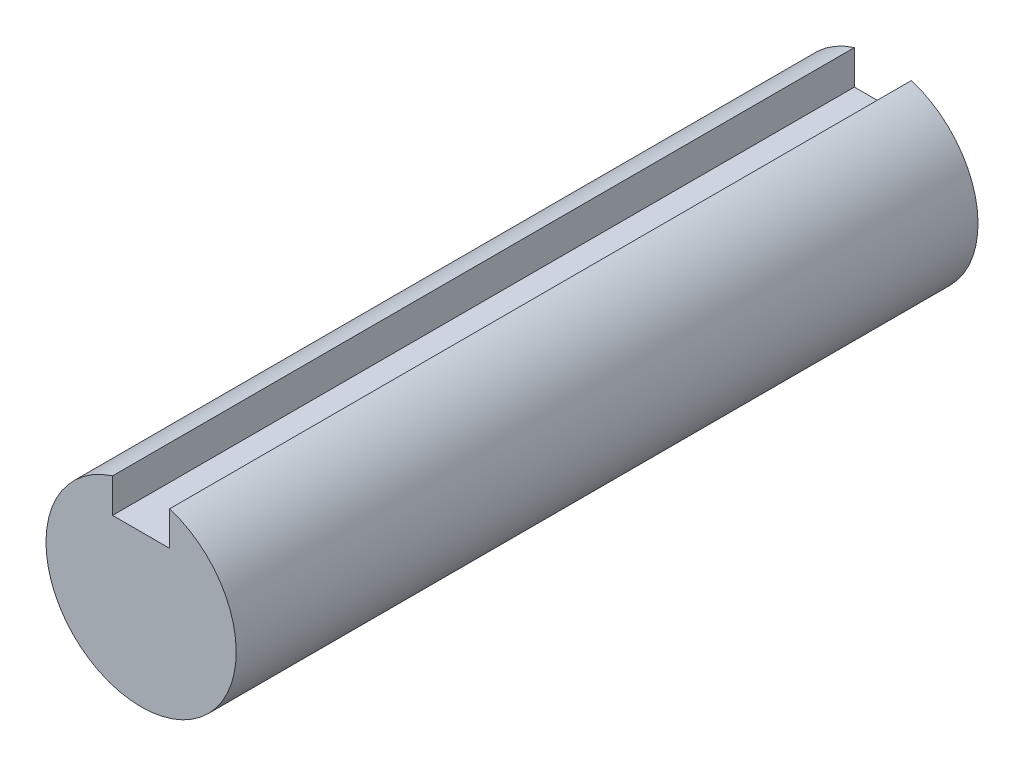
SolidWorks part; units mm, degrees
ref_plane "Piano frontale" through (0, 0, 0) normal (0, 0, 1) x (1, 0, 0)
ref_plane "Piano superiore" through (0, 0, 0) normal (0, 1, 0) x (1, 0, 0)
ref_plane "Piano destro" through (0, 0, 0) normal (1, 0, 0) x (0, 0, -1)
sketch "Schizzo1" plane through (0, 0, 0) normal (0, 0, 1) x (1, 0, 0)
  line L0 (0, 0) -> (0, 10.9071) construction
  line L1 (-1.5, 2.9697) -> (1.5, 2.9697)
  line L2 (1.5, 2.9697) -> (1.5, 4.7697)
  line L3 (-1.5, 2.9697) -> (-1.5, 4.7697)
  circle A0 centre (0, 0) radius 5
  point P7 (0, 2.9697)
  dimension "D1" = 10
  dimension "D2" = 1.8
  dimension "D3" = 3
extrude "Estrusione-Estrusione1" add sketch "Schizzo1" along normal blind 39
sketch "Schizzo2" plane through (0, 0, 39) normal (0, 0, 1) x (1, 0, 0)
  circle A0 centre (0, 0) radius 5
